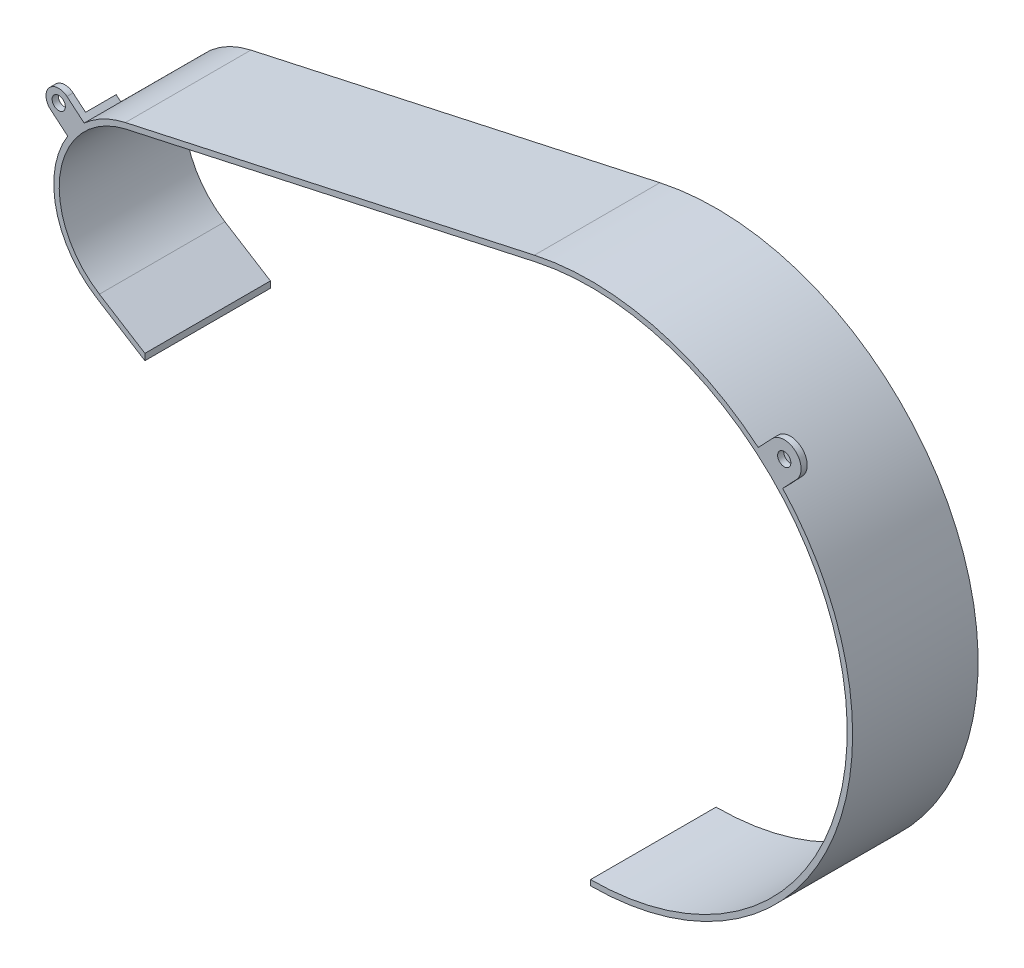
SolidWorks part; units mm, degrees
ref_plane "Front Plane" through (0, 0, 0) normal (0, 0, 1) x (1, 0, 0)
ref_plane "Top Plane" through (0, 0, 0) normal (0, 1, 0) x (1, 0, 0)
ref_plane "Right Plane" through (0, 0, 0) normal (1, 0, 0) x (0, 0, -1)
ref_plane "Plane1" through (0, 0, 61.5) normal (0, 0, 1) x (1, 0, 0)
ref_plane "Plane2" through (0, 0, 30.75) normal (0, 0, 1) x (1, 0, 0)
sketch "Sketch1" plane through (0, 0, 0) normal (0, 0, 1) x (1, 0, 0)
  line L0 (-6.8606, 95.0043) -> (191.7043, 141.5831) construction
  line L1 (-15.3604, 46.0483) -> (155.8828, -64.737) construction
  line L2 (-22.9887, 33.1233) -> (150.9206, -75.8029)
  line L3 (190.7626, 153.674) -> (-9.6857, 109.7441)
  line L4 (190.1932, 156.2724) -> (-10.2551, 112.3424)
  line L5 (-24.4006, 30.869) -> (149.5086, -78.0572)
  circle A0 centre (-0.6944, 68.7178) radius 27 construction
  circle A1 centre (217.6911, 30.8015) radius 113.7887 construction
  arc A2 (-9.6857, 109.7441) -> (-22.9887, 33.1233) centre (-0.6944, 68.7178) ccw
  arc A3 (150.9206, -75.8029) -> (190.7626, 153.674) centre (217.6911, 30.8015) ccw
  arc A4 (-10.2551, 112.3424) -> (-24.4006, 30.869) centre (-0.6944, 68.7178) ccw
  arc A5 (149.5086, -78.0572) -> (190.1932, 156.2724) centre (217.6911, 30.8015) ccw
  circle A6 centre (-0.6944, 68.7178) radius 27 construction
  arc A7 (156.4331, -65.0907) -> (192.3416, 141.7306) centre (217.6911, 30.8015) ccw construction
  dimension "D5" = 15
  dimension "D6" = 12
  dimension "D7" = 2.66
extrude "Boss-Extrude2" add sketch "Sketch1" along normal up to surface (61.5 mm away) up to plane "Plane1"
sketch "Sketch2" plane through (0, 0, 61.5) normal (0, 0, 1) x (1, 0, 0)
  line L1 (217.6911, -97.6472) -> (-0.6944, -97.6472)
  line L2 (217.6911, -97.6472) -> (217.6911, 26.7178)
  line L3 (217.6911, 26.7178) -> (-0.6944, 26.7178)
  line L4 (-0.6944, -97.6472) -> (-0.6944, 26.7178)
  line L5 (217.6911, -97.6472) -> (-0.6944, 26.7178) construction
  line L6 (217.6911, 26.7178) -> (-0.6944, -97.6472) construction
  circle A0 centre (-0.6944, 68.7178) radius 42 construction
  arc A1 (-9.6857, 109.7441) -> (-22.9887, 33.1233) centre (-0.6944, 68.7178) ccw construction
  circle A2 centre (217.6911, 30.8015) radius 125.7887 construction
  arc A3 (150.9206, -75.8029) -> (190.7626, 153.674) centre (217.6911, 30.8015) ccw construction
  arc A5 (149.5086, -78.0572) -> (190.1932, 156.2724) centre (217.6911, 30.8015) ccw construction
  point P12 (108.4984, -35.4647)
  point P17 (-0.6944, 26.7178)
  point P28 (217.6911, -94.9872)
extrude "Cut-Extrude1" cut sketch "Sketch2" against normal through all
ref_plane "Plane3" through (0, 68.7178, 0) normal (0, -1, 0) x (-1, 0, 0)
sketch "Sketch3" plane through (0, 0, 61.5) normal (0, 0, 1) x (1, 0, 0)
  line L0 (-42.9202, 104.2985) -> (-31.6801, 60.7249) construction
  line L1 (-31.6801, 60.7249) -> (-42.9202, 104.2985) construction
  line L2 (-46.9475, 99.519) -> (-38.5378, 92.4327)
  line L3 (-38.8929, 109.078) -> (-30.4831, 101.9917)
  line L4 (-38.5378, 92.4327) -> (-30.4831, 101.9917) construction
  line L5 (-55, 68.7178) -> (55, 68.7178) construction
  circle A0 centre (-0.6944, 68.7178) radius 32 construction
  circle A1 centre (-42.9202, 104.2985) radius 3.25
  arc A2 (-46.9475, 99.519) -> (-38.8929, 109.078) centre (-42.9202, 104.2985) cw
  arc A3 (-10.2551, 112.3424) -> (-24.4006, 30.869) centre (-0.6944, 68.7178) ccw construction
  arc A4 (-30.4831, 101.9917) -> (-38.5378, 92.4327) centre (-0.6944, 68.7178) ccw
  circle A9 centre (-42.9202, 104.2985) radius 3.25 construction
  point P6 (-32.6944, 68.7178)
  dimension "D1" = 64
  dimension "D2" = 6.5
  dimension "D3" = 3
extrude "Boss-Extrude3" add sketch "Sketch3" against normal blind 3
sketch "Sketch5" plane through (0, 0, 58.5) normal (0, 0, -1) x (-1, 0, 0)
  line L0 (32.7773, 103.9248) -> (40.8319, 94.3659)
  line L1 (30.4831, 101.9917) -> (38.8929, 109.078) construction
  line L2 (46.9475, 99.519) -> (38.5378, 92.4327) construction
  line L3 (32.7773, 103.9248) -> (30.4831, 101.9917)
  line L4 (30.4831, 101.9917) -> (38.5378, 92.4327)
  line L5 (38.5378, 92.4327) -> (40.8319, 94.3659)
  dimension "D1" = 3
extrude "Boss-Extrude4" add sketch "Sketch5" along normal blind 15
sketch "Sketch6" plane through (0, 0, 61.5) normal (0, 0, 1) x (1, 0, 0)
  line L0 (306.6284, 136.5963) -> (299.8985, 129.4981)
  line L1 (318.6022, 125.2438) -> (311.8723, 118.1456)
  line L2 (299.8985, 129.4981) -> (311.8723, 118.1456) construction
  line L3 (312.6153, 130.9201) -> (346.3704, 130.9201) construction
  circle A0 centre (312.6153, 130.9201) radius 3.25
  circle A1 centre (-42.9202, 104.2985) radius 3.25 construction
  arc A2 (306.6284, 136.5963) -> (318.6022, 125.2438) centre (312.6153, 130.9201) cw
  arc A3 (149.5086, -78.0572) -> (190.1932, 156.2724) centre (217.6911, 30.8015) ccw construction
  arc A4 (299.8985, 129.4981) -> (311.8723, 118.1456) centre (217.6911, 30.8015) cw
  dimension "D1" = 5
extrude "Boss-Extrude5" add sketch "Sketch6" against normal blind 3
